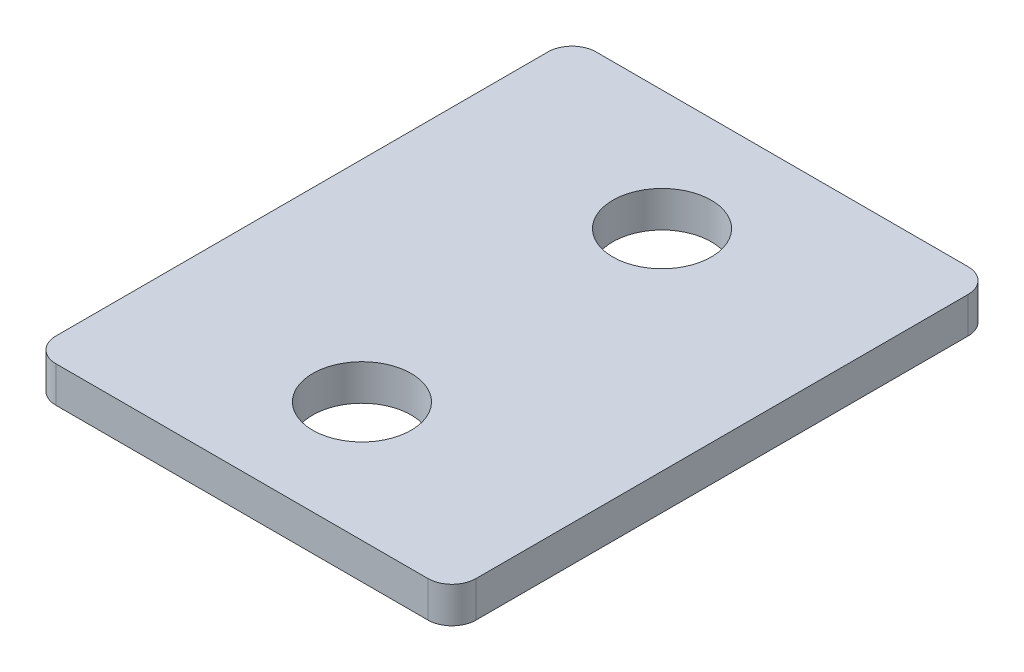
SolidWorks part; units mm, degrees
ref_plane "Front Plane" through (0, 0, 0) normal (0, 0, 1) x (1, 0, 0)
ref_plane "Top Plane" through (0, 0, 0) normal (0, 1, 0) x (1, 0, 0)
ref_plane "Right Plane" through (0, 0, 0) normal (1, 0, 0) x (0, 0, -1)
sketch "Sketch1" plane through (0, 0, 0) normal (0, 1, 0) x (1, 0, 0)
  line L0 (0, -12.5) -> (0, 12.5) construction
  line L1 (-15.5, -22.5) -> (15.5, -22.5)
  line L2 (-17.5, -20.5) -> (-17.5, 20.5)
  line L3 (-15.5, 22.5) -> (15.5, 22.5)
  line L4 (17.5, -20.5) -> (17.5, 20.5)
  line L5 (-17.5, -22.5) -> (17.5, 22.5) construction
  line L6 (-17.5, 22.5) -> (17.5, -22.5) construction
  line L7 (0, -8.4) -> (0, -16.6) construction
  arc A0 (-17.5, -20.5) -> (-15.5, -22.5) centre (-15.5, -20.5) ccw
  arc A1 (17.5, -20.5) -> (15.5, -22.5) centre (15.5, -20.5) cw
  arc A2 (15.5, 22.5) -> (17.5, 20.5) centre (15.5, 20.5) cw
  arc A3 (-15.5, 22.5) -> (-17.5, 20.5) centre (-15.5, 20.5) ccw
  circle A4 centre (0, 12.5) radius 4.1
  circle A5 centre (0, -12.5) radius 4.1
  point P0 (0, 0)
  point P19 (0, 0)
  dimension "D3" = 2
  dimension "D4" = 8.2
  dimension "D5" = 8.2
  dimension "D1" = 35
  dimension "D2" = 45
  dimension "D6" = 25
extrude "Boss-Extrude1" add sketch "Sketch1" along normal blind 3
